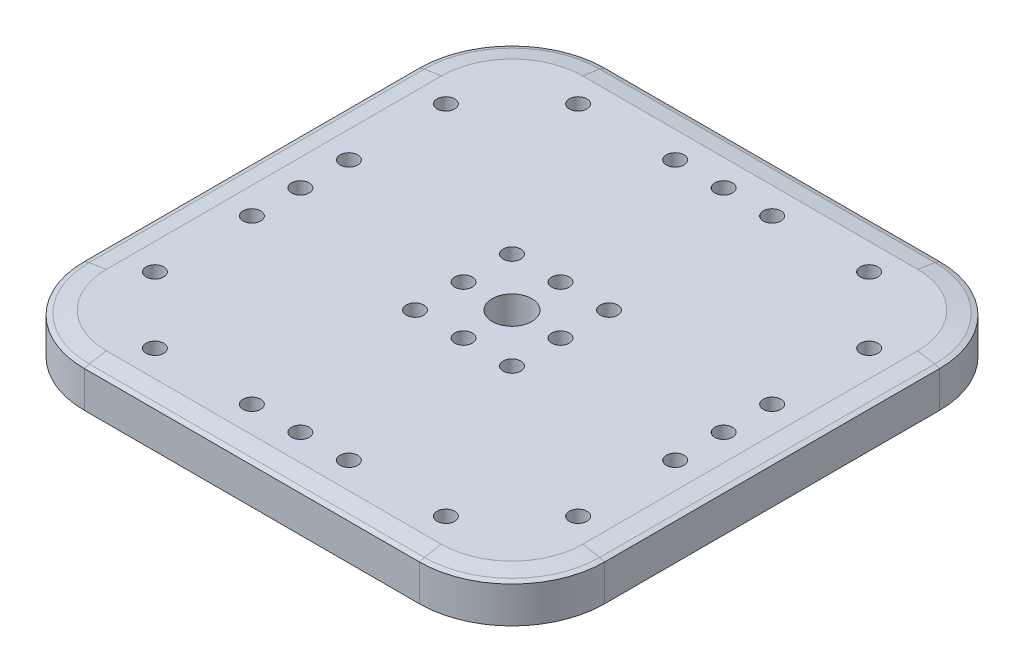
SolidWorks part; units mm, degrees
ref_plane "Front Plane" through (0, 0, 0) normal (0, 0, 1) x (1, 0, 0)
ref_plane "Top Plane" through (0, 0, 0) normal (0, 1, 0) x (1, 0, 0)
ref_plane "Right Plane" through (0, 0, 0) normal (1, 0, 0) x (0, 0, -1)
sketch "Sketch1" plane through (0, 0, 0) normal (0, 1, 0) x (1, 0, 0)
  line L1 (-59, -59) -> (59, -59)
  line L2 (-59, -59) -> (-59, 59)
  line L3 (-59, 59) -> (59, 59)
  line L4 (59, -59) -> (59, 59)
  line L5 (-59, -59) -> (59, 59) construction
  line L6 (-59, 59) -> (59, -59) construction
  circle A0 centre (0, 0) radius 4.5
  point P0 (0, 0)
extrude "Boss-Extrude1" add sketch "Sketch1" along normal blind 9.85
sketch "Sketch2" plane through (0, 9.85, 0) normal (0, 1, 0) x (1, 0, 0)
  line L0 (0, 0) -> (0, -48) construction
  line L1 (-11, -48) -> (11, -48) construction
  line L2 (11, -48) -> (33, -48) construction
  line L3 (-11, -48) -> (-33, -48) construction
  line L4 (0, 0) -> (0, -11) construction
  line L5 (-11, -11) -> (11, -11) construction
  line L6 (0, 0) -> (-11, 0) construction
  line L7 (-11, 48) -> (-33, 48) construction
  line L8 (11, 48) -> (33, 48) construction
  line L9 (-11, 48) -> (11, 48) construction
  line L10 (-59, 59) -> (59, -59) construction
  line L11 (48, 11) -> (48, 33) construction
  line L12 (48, -11) -> (48, -33) construction
  line L13 (48, 11) -> (48, -11) construction
  line L14 (-48, 11) -> (-48, -11) construction
  line L15 (-48, -11) -> (-48, -33) construction
  line L16 (-48, 11) -> (-48, 33) construction
  circle A0 centre (0, -48) radius 2
  circle A1 centre (11, -48) radius 2
  circle A2 centre (33, -48) radius 2
  circle A3 centre (-33, -48) radius 2
  circle A4 centre (-11, -48) radius 2
  circle A5 centre (0, -11) radius 2
  circle A6 centre (11, -11) radius 2
  circle A7 centre (-11, -11) radius 2
  circle A8 centre (-11, 0) radius 2
  circle A9 centre (-11, 11) radius 2
  circle A10 centre (11, 11) radius 2
  circle A11 centre (0, 11) radius 2
  circle A12 centre (-11, 48) radius 2
  circle A13 centre (-33, 48) radius 2
  circle A14 centre (33, 48) radius 2
  circle A15 centre (11, 48) radius 2
  circle A16 centre (0, 48) radius 2
  circle A17 centre (11, 0) radius 2
  circle A18 centre (48, 11) radius 2
  circle A19 centre (48, 33) radius 2
  circle A20 centre (48, -33) radius 2
  circle A21 centre (48, -11) radius 2
  circle A22 centre (48, 0) radius 2
  circle A23 centre (-48, 0) radius 2
  circle A24 centre (-48, -11) radius 2
  circle A25 centre (-48, -33) radius 2
  circle A26 centre (-48, 33) radius 2
  circle A27 centre (-48, 11) radius 2
  dimension "D4" = 11
  dimension "D1" = 48
  dimension "D2" = 11
  dimension "D3" = 22
extrude "Cut-Extrude1" cut sketch "Sketch2" against normal blind 5
fillet "Fillet1" radius 21 4 edges at (59, 4.925, -59) (-59, 4.925, -59) (-59, 4.925, 59) (59, 4.925, 59)
chamfer "Chamfer1" distance 2 angle 18 8 edges at (59, 0, 0) (52.8492, 0, -52.8492) (52.8492, 0, 52.8492) (0, 0, -59) (0, 0, 59) (-52.8492, 0, -52.8492) (-52.8492, 0, 52.8492) (-59, 0, 0)
chamfer "Chamfer2" distance 3 angle 18 8 edges at (52.8492, 9.85, -52.8492) (0, 9.85, -59) (59, 9.85, 0) (-52.8492, 9.85, -52.8492) (52.8492, 9.85, 52.8492) (-59, 9.85, 0) (0, 9.85, 59) (-52.8492, 9.85, 52.8492)
chamfer "Chamfer3" distance 2 8 edges at (50.7279, 9.85, 50.7279) (0, 9.85, 56) (-50.7279, 9.85, 50.7279) (-56, 9.85, 0) (-50.7279, 9.85, -50.7279) (0, 9.85, -56) (50.7279, 9.85, -50.7279) (56, 9.85, 0)
thread "Thread1" [suppressed] pitch 0.7 start angle 0, offset 1, length 0, pitch 0.7, diameter 4
ref_plane "Plane1" through (-50, 10.85, 33) normal (0, 0, 1) x (-1, 0, 0)
sketch "Thread Profile1" plane through (-50, 10.85, 33) normal (0, 0, 1) x (-1, 0, 0)
  line L0 (0, 0) -> (0, 0.7) construction
  line L1 (0, 0) -> (0.3789, 0.2187)
  line L2 (0.3789, 0.2187) -> (0.3789, 0.3062)
  line L3 (0.3789, 0.3062) -> (0, 0.525)
  line L4 (0.3789, 0.2625) -> (0, 0.2625) construction
  line L11 (0, 0) -> (0, 0.525)
  point P2 (0, 0)
  dimension "Pitch" = 0.7
  dimension "Profile_Angle" = 60
  dimension "Profile_Land" = 0.0875
  dimension "Profile_Height" = 0.3789
thread "Thread2" [suppressed] pitch 0.7 start angle 0, offset 1, length 0, pitch 0.7, diameter 4
ref_plane "Plane2" through (-50, 10.85, 11) normal (0, 0, 1) x (-1, 0, 0)
sketch "Thread Profile2" plane through (-50, 10.85, 11) normal (0, 0, 1) x (-1, 0, 0)
  line L0 (0, 0) -> (0, 0.7) construction
  line L1 (0, 0) -> (0.3789, 0.2187)
  line L2 (0.3789, 0.2187) -> (0.3789, 0.3062)
  line L3 (0.3789, 0.3062) -> (0, 0.525)
  line L4 (0.3789, 0.2625) -> (0, 0.2625) construction
  line L11 (0, 0) -> (0, 0.525)
  point P2 (0, 0)
  dimension "Pitch" = 0.7
  dimension "Profile_Angle" = 60
  dimension "Profile_Land" = 0.0875
  dimension "Profile_Height" = 0.3789
thread "Thread3" [suppressed] pitch 0.7 start angle 0, offset 1, length 0, pitch 0.7, diameter 4
ref_plane "Plane3" through (-50, 10.85, 0) normal (0, 0, 1) x (-1, 0, 0)
sketch "Thread Profile3" plane through (-50, 10.85, 0) normal (0, 0, 1) x (-1, 0, 0)
  line L0 (0, 0) -> (0, 0.7) construction
  line L1 (0, 0) -> (0.3789, 0.2187)
  line L2 (0.3789, 0.2187) -> (0.3789, 0.3062)
  line L3 (0.3789, 0.3062) -> (0, 0.525)
  line L4 (0.3789, 0.2625) -> (0, 0.2625) construction
  line L11 (0, 0) -> (0, 0.525)
  point P2 (0, 0)
  dimension "Pitch" = 0.7
  dimension "Profile_Angle" = 60
  dimension "Profile_Land" = 0.0875
  dimension "Profile_Height" = 0.3789
mirror "Mirror1" [suppressed] about plane through (0, 0, 0) normal (1, 0, 0)
ref_plane "Plane4" through (0, 0, 0) normal (0.7071, 0, -0.7071) x (-0.7071, 0, -0.7071)
mirror "Mirror2" [suppressed] about plane through (0, 0, 0) normal (0.7071, 0, -0.7071)
thread "Thread4" [suppressed] pitch 0.7 start angle 0, offset 1, length 0, pitch 0.7, diameter 4
ref_plane "Plane5" through (-13, 10.85, 11) normal (0, 0, 1) x (-1, 0, 0)
sketch "Thread Profile4" plane through (-13, 10.85, 11) normal (0, 0, 1) x (-1, 0, 0)
  line L0 (0, 0) -> (0, 0.7) construction
  line L1 (0, 0) -> (0.3789, 0.2187)
  line L2 (0.3789, 0.2187) -> (0.3789, 0.3062)
  line L3 (0.3789, 0.3062) -> (0, 0.525)
  line L4 (0.3789, 0.2625) -> (0, 0.2625) construction
  line L11 (0, 0) -> (0, 0.525)
  point P2 (0, 0)
  dimension "Pitch" = 0.7
  dimension "Profile_Angle" = 60
  dimension "Profile_Land" = 0.0875
  dimension "Profile_Height" = 0.3789
thread "Thread5" [suppressed] pitch 0.7 start angle 0, offset 1, length 0, pitch 0.7, diameter 4
ref_plane "Plane6" through (9, 10.85, 11) normal (0, 0, 1) x (-1, 0, 0)
sketch "Thread Profile5" plane through (9, 10.85, 11) normal (0, 0, 1) x (-1, 0, 0)
  line L0 (0, 0) -> (0, 0.7) construction
  line L1 (0, 0) -> (0.3789, 0.2187)
  line L2 (0.3789, 0.2187) -> (0.3789, 0.3062)
  line L3 (0.3789, 0.3062) -> (0, 0.525)
  line L4 (0.3789, 0.2625) -> (0, 0.2625) construction
  line L11 (0, 0) -> (0, 0.525)
  point P2 (0, 0)
  dimension "Pitch" = 0.7
  dimension "Profile_Angle" = 60
  dimension "Profile_Land" = 0.0875
  dimension "Profile_Height" = 0.3789
mirror "Mirror3" [suppressed] about plane through (0, 0, 0) normal (0, 0, 1)
sketch "Sketch3" plane through (0, 9.85, 0) normal (0, 1, 0) x (1, 0, 0)
  line L0 (0, 0) -> (33, 48) construction
  line L1 (0, 0) -> (57.9021, 0) construction
  line L2 (57.9021, 38) -> (57.9021, -38) construction
  dimension "D1" = 58.2495
  dimension "D2" = 55.491
